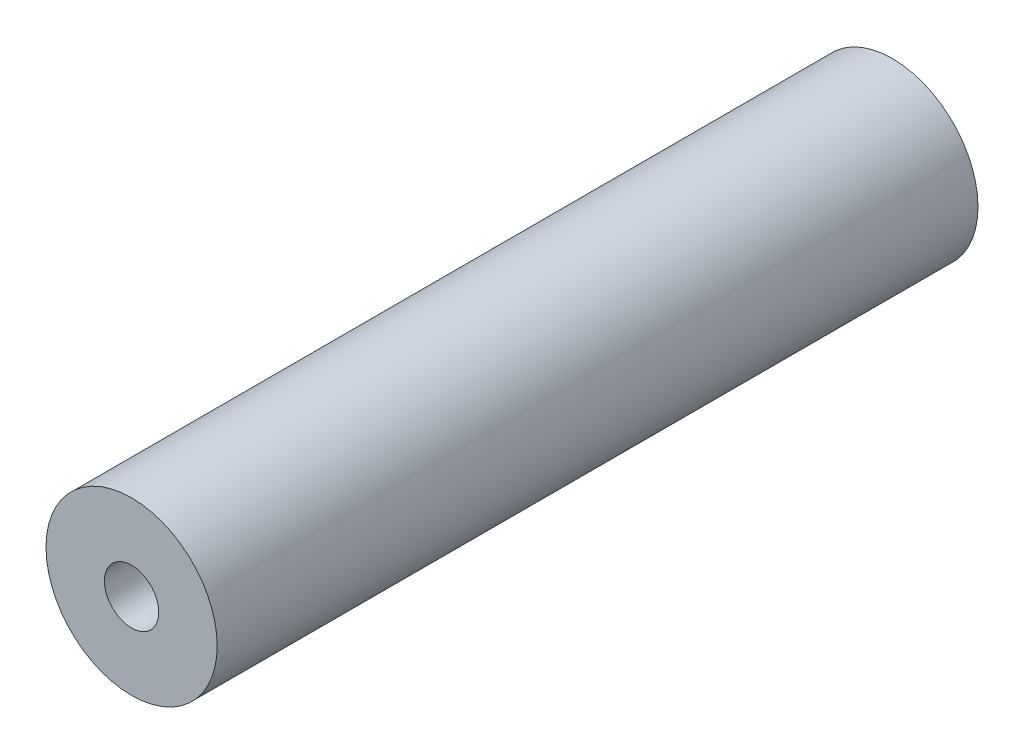
SolidWorks part; units mm, degrees
material "Полиэфирная смола"
ref_plane "Спереди" through (0, 0, 0) normal (0, 0, 1) x (1, 0, 0)
ref_plane "Сверху" through (0, 0, 0) normal (0, 1, 0) x (1, 0, 0)
ref_plane "Справа" through (0, 0, 0) normal (1, 0, 0) x (0, 0, -1)
sketch "Эскиз1" plane through (0, 0, 0) normal (0, 0, 1) x (1, 0, 0)
  circle A0 centre (0, 0) radius 3.15
  circle A1 centre (0, 0) radius 1
  dimension "D1" = 6.3
  dimension "D2" = 2
  dimension "D3" = 2.15
extrude "Бобышка-Вытянуть1" add sketch "Эскиз1" along normal blind 28
